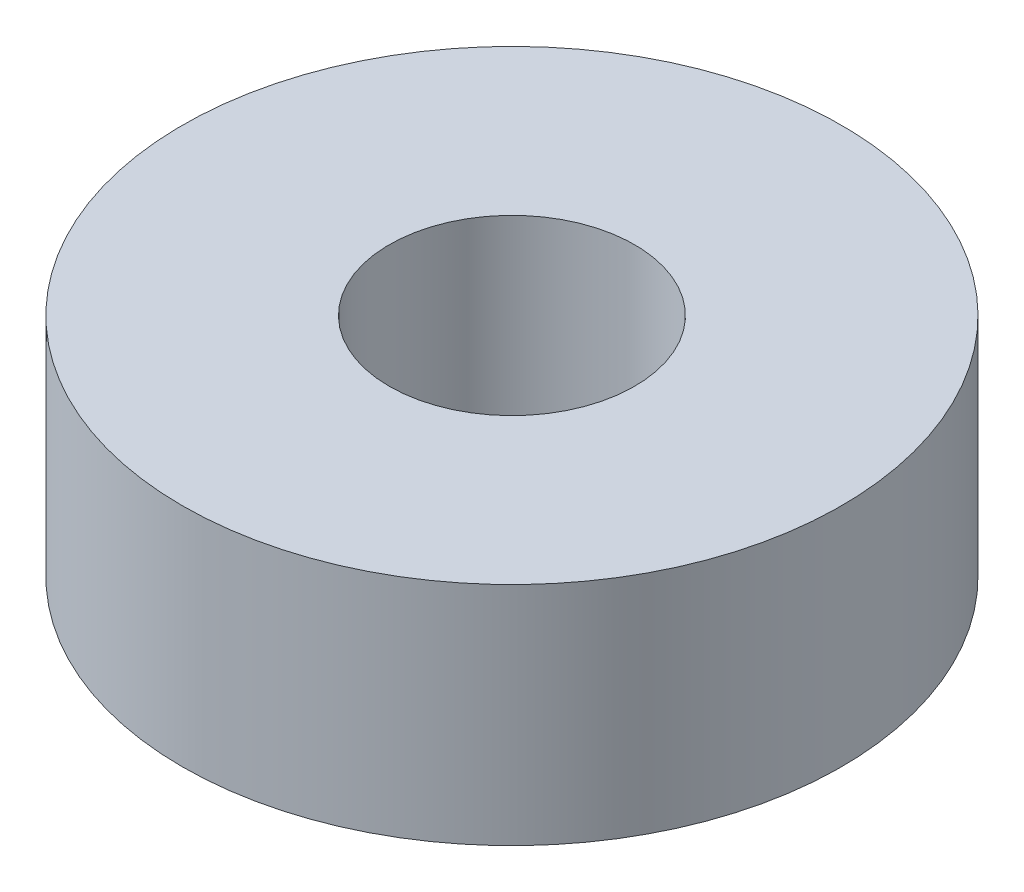
SolidWorks part; units mm, degrees
ref_plane "Front Plane" through (0, 0, 0) normal (0, 0, 1) x (1, 0, 0)
ref_plane "Top Plane" through (0, 0, 0) normal (0, 1, 0) x (1, 0, 0)
ref_plane "Right Plane" through (0, 0, 0) normal (1, 0, 0) x (0, 0, -1)
sketch "Sketch1" plane through (0, 0, 0) normal (0, 1, 0) x (1, 0, 0)
  circle A0 centre (0, 0) radius 6.85
  circle A1 centre (0, 0) radius 2.55
  dimension "D1" = 13.7
  dimension "D2" = 5.1
extrude "Boss-Extrude1" add sketch "Sketch1" along normal blind 4.7
ref_point "Point1"
